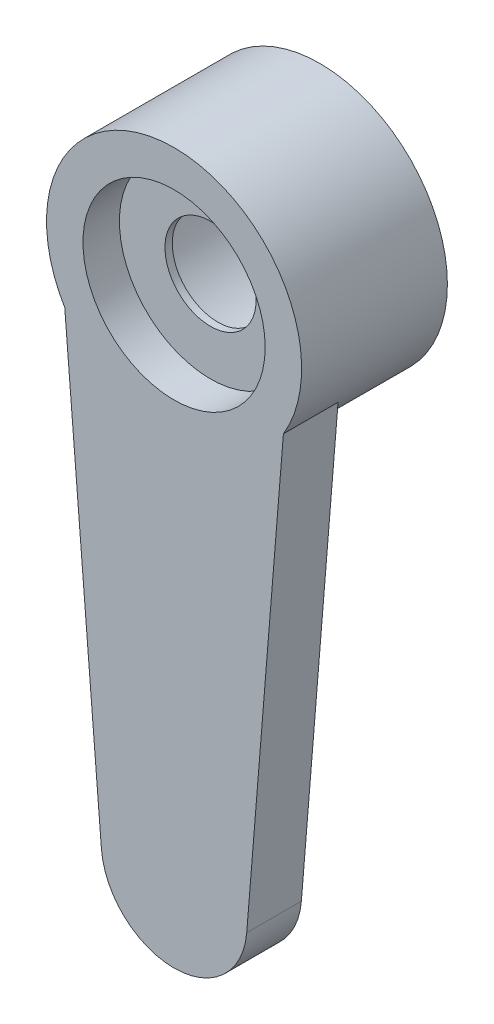
SolidWorks part; units mm, degrees
material "ABS"
ref_plane "Front" through (0, 0, 0) normal (0, 0, 1) x (1, 0, 0)
ref_plane "Top" through (0, 0, 0) normal (0, 1, 0) x (1, 0, 0)
ref_plane "Right" through (0, 0, 0) normal (1, 0, 0) x (0, 0, -1)
sketch "Sketch1" plane through (0, 0, 0) normal (0, 0, 1) x (1, 0, 0)
  circle A0 centre (0, 0) radius 3.5
  circle A1 centre (0, 0) radius 2.5
  dimension "D1" = 7
  dimension "D2" = 5
extrude "Boss-Extrude1" add sketch "Sketch1" along normal blind 2.8
sketch "Sketch2" plane through (0, 0, 2.8) normal (0, 0, 1) x (1, 0, 0)
  circle A0 centre (0, 0) radius 3.5
  circle A1 centre (0, 0) radius 1.25
  dimension "D1" = 2.5
extrude "Boss-Extrude2" add sketch "Sketch2" along normal blind 0.2
sketch "Sketch3" plane through (0, 0, 3) normal (0, 0, 1) x (1, 0, 0)
  circle A0 centre (0, 0) radius 3.5
  circle A1 centre (0, 0) radius 2.5
  dimension "D1" = 5
extrude "Boss-Extrude3" add sketch "Sketch3" along normal blind 1
sketch "Sketch4" plane through (0, 0, 4) normal (0, 0, 1) x (1, 0, 0)
  line L0 (-3, -1.8028) -> (-1.9934, -14.1623)
  line L1 (3, -1.8028) -> (1.9934, -14.1623)
  circle A0 centre (0, 0) radius 3.5 construction
  arc A1 (-1.9934, -14.1623) -> (1.9934, -14.1623) centre (0, -14) ccw
  arc A2 (-3, -1.8028) -> (3, -1.8028) centre (0, 0) ccw
  point P7 (3, -1.8028)
  point P8 (0, 0)
  dimension "D2" = 16
  dimension "D3" = 2
  dimension "D1" = 6
extrude "Boss-Extrude4" add sketch "Sketch4" against normal blind 1.5
